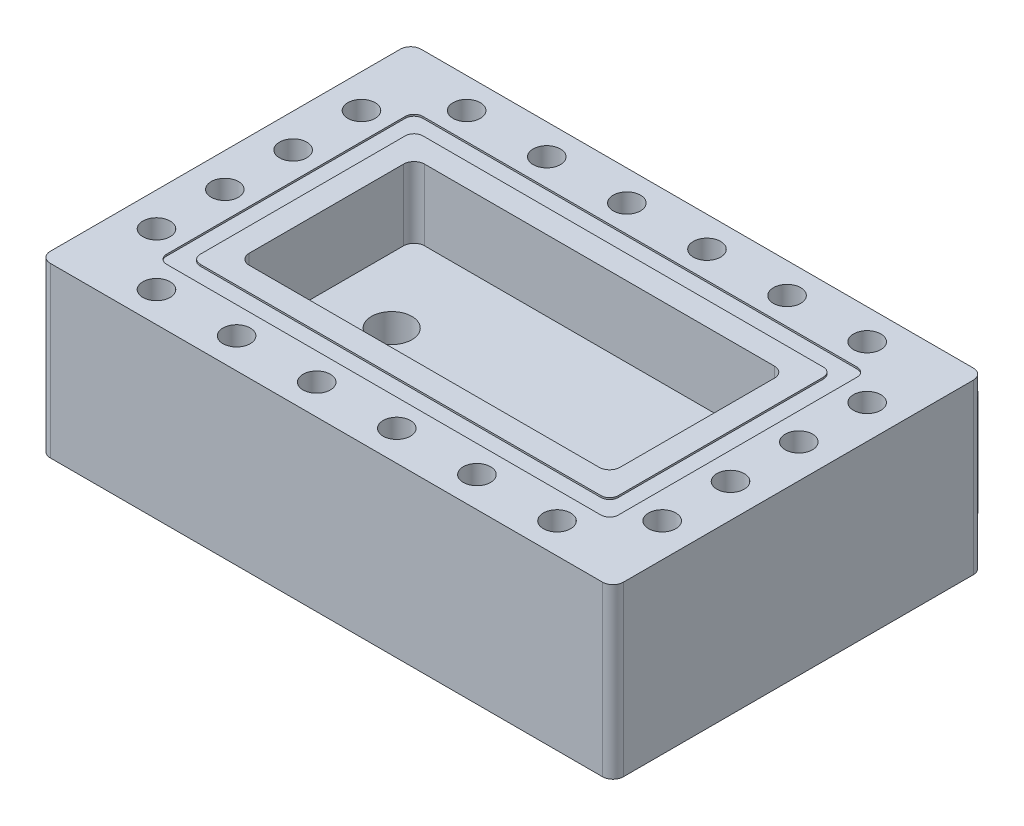
SolidWorks part; units mm, degrees
ref_plane "Front Plane" through (0, 0, 0) normal (0, 0, 1) x (1, 0, 0)
ref_plane "Top Plane" through (0, 0, 0) normal (0, 1, 0) x (1, 0, 0)
ref_plane "Right Plane" through (0, 0, 0) normal (1, 0, 0) x (0, 0, -1)
sketch "Sketch1" plane through (0, 0, 0) normal (0, 1, 0) x (1, 0, 0)
  line L0 (80, 55) -> (85, 55)
  line L1 (0, 0) -> (85, 0)
  line L2 (0, 0) -> (0, 55)
  line L3 (0, 55) -> (60, 55)
  line L4 (85, 0) -> (85, 55)
  line L5 (70, 55) -> (70, 65) construction
  arc A0 (60, 55) -> (80, 55) centre (70, 55) cw
  circle A1 centre (70, 60) radius 2
  dimension "D3" = 10
  dimension "D5" = 4
  dimension "D1" = 85
  dimension "D2" = 55
  dimension "D4" = 25
extrude "Boss-Extrude1" add sketch "Sketch1" along normal blind 25
sketch "Sketch2" plane through (0, 25, 0) normal (0, 1, 0) x (1, 0, 0)
  line L0 (42.5, 14.5) -> (42.5, 0) construction
  line L1 (15, 40.5) -> (70, 40.5)
  line L2 (15, 40.5) -> (15, 14.5)
  line L3 (15, 14.5) -> (70, 14.5)
  line L4 (70, 40.5) -> (70, 14.5)
  line L5 (0, 0) -> (85, 0) construction
  line L6 (70, 27.5) -> (85, 27.5) construction
  line L7 (85, 0) -> (85, 55) construction
  line L8 (15, 27.5) -> (0, 27.5) construction
  line L9 (0, 55) -> (0, 0) construction
  line L10 (42.5, 40.5) -> (42.5, 55) construction
  line L12 (42.5, 55) -> (85, 55) construction
  dimension "D1" = 26
  dimension "D2" = 55
extrude "Cut-Extrude1" cut sketch "Sketch2" against normal blind 10.5
fillet "Fillet1" radius 1.55 10 edges at (15, 19.75, -40.5) (15, 19.75, -14.5) (70, 19.75, -14.5) (70, 19.75, -40.5) (0, 12.5, -55) (85, 12.5, 0) (0, 12.5, 0) (60, 12.5, -55) (80, 12.5, -55) (85, 12.5, -55)
sketch "Sketch3" plane through (0, 25, 0) normal (0, 1, 0) x (1, 0, 0)
  line L0 (42.5, 14.5) -> (42.5, 11) construction
  line L1 (11.5, 44) -> (73.5, 44)
  line L2 (11.5, 44) -> (11.5, 11)
  line L3 (11.5, 11) -> (73.5, 11)
  line L4 (73.5, 44) -> (73.5, 11)
  line L5 (9, 46.5) -> (76, 46.5)
  line L6 (9, 46.5) -> (9, 8.5)
  line L7 (9, 8.5) -> (76, 8.5)
  line L8 (76, 46.5) -> (76, 8.5)
  line L9 (16.55, 14.5) -> (68.45, 14.5) construction
  line L10 (42.5, 11) -> (42.5, 8.5) construction
  line L11 (42.5, 40.5) -> (42.5, 44) construction
  line L12 (68.45, 40.5) -> (16.55, 40.5) construction
  line L13 (42.5, 44) -> (42.5, 46.5) construction
  line L14 (70, 27.5) -> (73.5, 27.5) construction
  line L15 (70, 16.05) -> (70, 38.95) construction
  line L16 (73.5, 27.5) -> (76, 27.5) construction
  line L17 (15, 27.5) -> (11.5, 27.5) construction
  line L18 (15, 38.95) -> (15, 16.05) construction
  line L19 (11.5, 27.5) -> (9, 27.5) construction
  dimension "D1" = 2.5
  dimension "D2" = 62
extrude "Cut-Extrude2" cut sketch "Sketch3" against normal blind 0.25
fillet "Fillet2" radius 1.3 8 edges at (76, 24.875, -46.5) (73.5, 24.875, -44) (73.5, 24.875, -11) (76, 24.875, -8.5) (11.5, 24.875, -11) (9, 24.875, -8.5) (11.5, 24.875, -44) (9, 24.875, -46.5)
sketch "Sketch5" plane through (0, 25, 0) normal (0, 1, 0) x (1, 0, 0)
  line L0 (12.8, 50.5) -> (5, 42.7) construction
  line L1 (5, 42.7) -> (5, 32.5667) construction
  line L2 (5, 32.5667) -> (5, 22.4333) construction
  line L3 (5, 22.4333) -> (5, 12.3) construction
  line L4 (5, 12.3) -> (12.8, 4.5) construction
  line L5 (12.8, 4.5) -> (24.68, 4.5) construction
  line L7 (24.68, 4.5) -> (36.56, 4.5) construction
  line L8 (36.56, 4.5) -> (48.44, 4.5) construction
  line L9 (48.44, 4.5) -> (60.32, 4.5) construction
  line L10 (60.32, 4.5) -> (72.2, 4.5) construction
  line L11 (72.2, 4.5) -> (80, 12.3) construction
  line L12 (80, 12.3) -> (80, 22.4333) construction
  line L13 (80, 22.4333) -> (80, 32.5667) construction
  line L14 (80, 32.5667) -> (80, 42.7) construction
  line L15 (80, 42.7) -> (72.2, 50.5) construction
  line L16 (72.2, 50.5) -> (60.32, 50.5) construction
  line L17 (60.32, 50.5) -> (48.44, 50.5) construction
  line L18 (48.44, 50.5) -> (36.56, 50.5) construction
  line L19 (36.56, 50.5) -> (24.68, 50.5) construction
  line L20 (24.68, 50.5) -> (12.8, 50.5) construction
  line L21 (42.5, 8.5) -> (42.5, 4.5) construction
  line L24 (10.3, 8.5) -> (74.7, 8.5) construction
  line L25 (42.5, 50.5) -> (42.5, 46.5) construction
  line L26 (74.7, 46.5) -> (10.3, 46.5) construction
  line L27 (5, 27.5) -> (9, 27.5) construction
  line L28 (9, 45.2) -> (9, 9.8) construction
  line L29 (76, 27.5) -> (80, 27.5) construction
  line L30 (76, 9.8) -> (76, 45.2) construction
  line L31 (12.8, 11) -> (12.8, 4.5) construction
  line L32 (11.5, 12.3) -> (5, 12.3) construction
  circle A0 centre (5, 42.7) radius 2.025
  circle A1 centre (5, 12.3) radius 2.025
  circle A2 centre (12.8, 4.5) radius 2.025
  circle A3 centre (72.2, 4.5) radius 2.025
  circle A5 centre (24.68, 4.5) radius 2.025
  circle A6 centre (36.56, 4.5) radius 2.025
  circle A7 centre (48.44, 4.5) radius 2.025
  circle A8 centre (60.32, 4.5) radius 2.025
  circle A9 centre (5, 32.5667) radius 2.025
  circle A10 centre (5, 22.4333) radius 2.025
  circle A11 centre (80, 42.7) radius 2.025
  circle A12 centre (80, 12.3) radius 2.025
  circle A13 centre (80, 22.4333) radius 2.025
  circle A14 centre (80, 32.5667) radius 2.025
  circle A15 centre (12.8, 50.5) radius 2.025
  circle A16 centre (24.68, 50.5) radius 2.025
  circle A17 centre (36.56, 50.5) radius 2.025
  circle A18 centre (48.44, 50.5) radius 2.025
  circle A19 centre (60.32, 50.5) radius 2.025
  circle A20 centre (72.2, 50.5) radius 2.025
  dimension "D2" = 4.05
  dimension "D1" = 4
extrude "Cut-Extrude4" cut sketch "Sketch5" against normal through all
sketch "Sketch6" plane through (0, 14.5, 0) normal (0, 1, 0) x (1, 0, 0)
  line L0 (24.68, 50.5) -> (24.68, 4.5) construction
  circle A0 centre (24.68, 27.5) radius 3
  dimension "D1" = 6
extrude "Cut-Extrude5" cut sketch "Sketch6" against normal through all
sketch "Sketch7" plane through (0, 25, 0) normal (0, 1, 0) x (1, 0, 0)
  line L0 (58.5545, 55) -> (81.4455, 55)
  arc A0 (60.0905, 56.342) -> (79.9095, 56.342) centre (70, 55) cw
  arc A1 (79.9095, 56.342) -> (60.0905, 56.342) centre (70, 55) ccw construction
  arc A2 (79.9095, 56.342) -> (81.4455, 55) centre (81.4455, 56.55) ccw
  arc A3 (58.5545, 55) -> (60.0905, 56.342) centre (58.5545, 56.55) ccw
extrude "Cut-Extrude6" cut sketch "Sketch7" against normal blind 10
